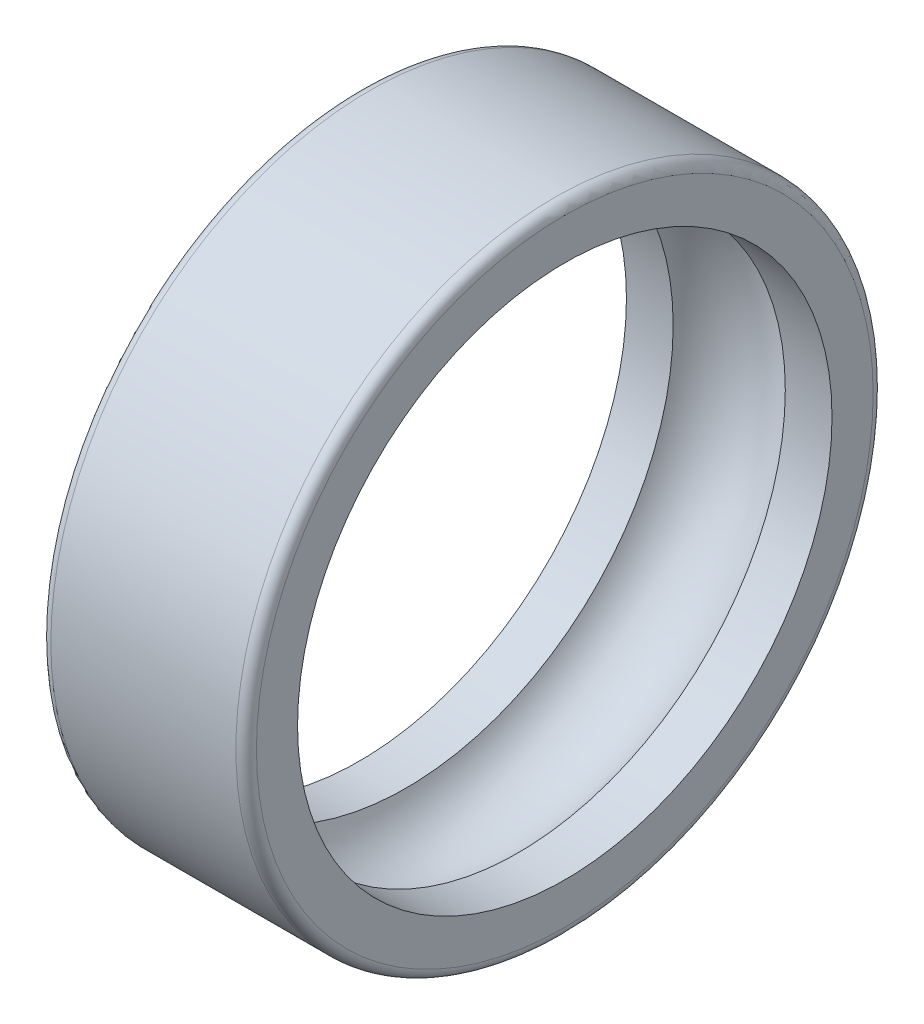
SolidWorks part; units mm, degrees
ref_plane "Front Plane" through (0, 0, 0) normal (0, 0, 1) x (1, 0, 0)
ref_plane "Top Plane" through (0, 0, 0) normal (0, 1, 0) x (1, 0, 0)
ref_plane "Right Plane" through (0, 0, 0) normal (1, 0, 0) x (0, 0, -1)
sketch "Sketch1" plane through (0, 0, 0) normal (0, 0, 1) x (1, 0, 0)
  line L0 (30.3093, 0) -> (-35.4639, 0) construction
  line L1 (0, 0) -> (0, 28.5) construction
  line L2 (10, 31) -> (-10, 31)
  line L3 (10, 31) -> (10, 26)
  line L4 (10, 26) -> (5.4544, 26)
  line L5 (-10, 31) -> (-10, 26)
  line L6 (10, 31) -> (-10, 26) construction
  line L7 (10, 26) -> (-10, 31) construction
  line L8 (-5.4544, 26) -> (-10, 26)
  arc A0 (-5.4544, 26) -> (5.4544, 26) centre (0, 23.5) cw
  point P3 (0, 28.5)
  dimension "D5" = 6
  dimension "D1" = 20
  dimension "D2" = 52
  dimension "D3" = 62
  dimension "D4" = 5
revolve "Revolve1" add sketch "Sketch1" angle 360 about L0
fillet "Fillet1" radius 1 2 edges at (10, 0, -31) (-10, 0, -31)
